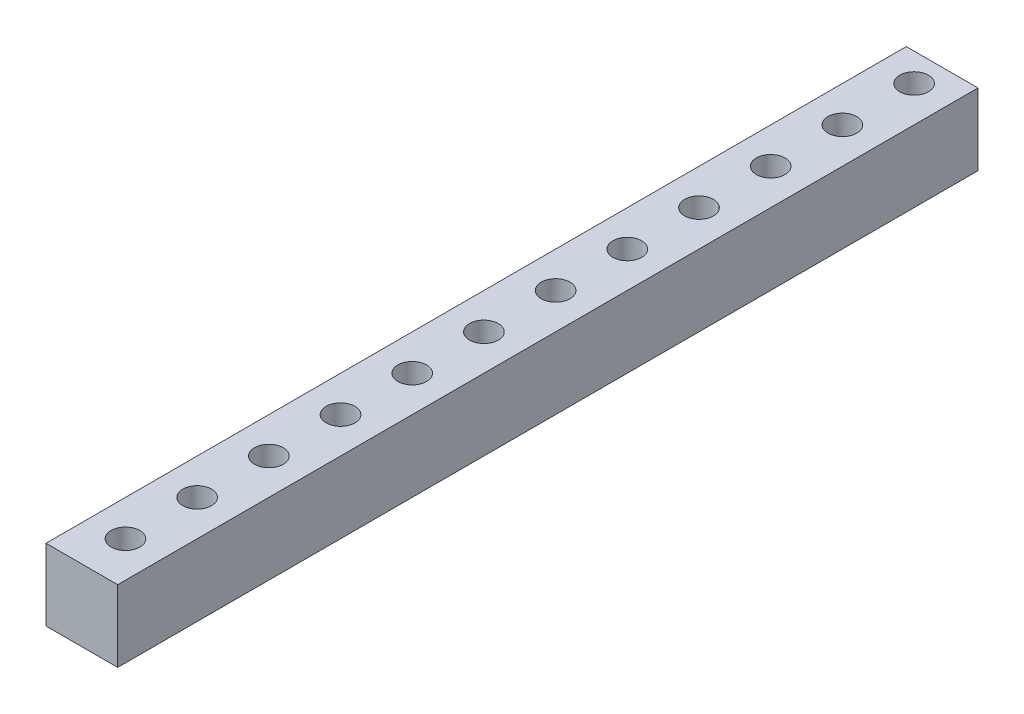
SolidWorks part; units mm, degrees
ref_plane "Front Plane" through (0, 0, 0) normal (0, 0, 1) x (1, 0, 0)
ref_plane "Top Plane" through (0, 0, 0) normal (0, 1, 0) x (1, 0, 0)
ref_plane "Right Plane" through (0, 0, 0) normal (1, 0, 0) x (0, 0, -1)
sketch "Sketch1" plane through (0, 0, 0) normal (1, 0, 0) x (0, 0, -1)
  line L1 (-15.24, -1.27) -> (15.24, -1.27)
  line L2 (-15.24, -1.27) -> (-15.24, 1.27)
  line L3 (-15.24, 1.27) -> (15.24, 1.27)
  line L4 (15.24, -1.27) -> (15.24, 1.27)
  line L5 (-15.24, -1.27) -> (15.24, 1.27) construction
  line L6 (-15.24, 1.27) -> (15.24, -1.27) construction
  point P0 (0, 0)
  dimension "D1" = 30.48
  dimension "D2" = 2.54
extrude "Boss-Extrude1" add sketch "Sketch1" along normal blind 2.54
sketch "Sketch2" plane through (0, 1.27, 0) normal (0, 1, 0) x (1, 0, 0)
  line L0 (1.27, 15.24) -> (1.27, -15.24) construction
  line L3 (2.54, 15.24) -> (0, 15.24) construction
  line L4 (2.54, -15.24) -> (0, -15.24) construction
  line L5 (1.27, -15.24) -> (1.27, -13.6951)
hole_wizard "Ø1.0mm Dowel Hole2" positions "Sketch4" profile "Sketch5" hole size "Ø1.0" standard "ANSI Metric" end condition through all
sketch "Sketch4" plane through (0, 1.27, 0) normal (0, 1, 0) x (1, 0, 0)
  point P0 (1.27, -13.6951)
sketch "Sketch5" plane through (1.27, 1.27, 13.6951) normal (1, 0, 0) x (0, 0, 1)
  line L0 (0, 0) -> (0, 2.54)
  line L1 (0, 2.54) -> (0.51, 2.54)
  line L2 (0.51, 2.54) -> (0.51, 0)
  line L5 (0.51, 0) -> (0, 0)
  line L11 (0, -6.35) -> (0, 107.95) construction
  dimension "Thru Hole Dia." = 1.02
  dimension "Thru Hole Depth" = 2.54
pattern_linear "LPattern2" count 12 spacing 2.54 along (0, 0, -1) of "Ø1.0mm Dowel Hole2"
